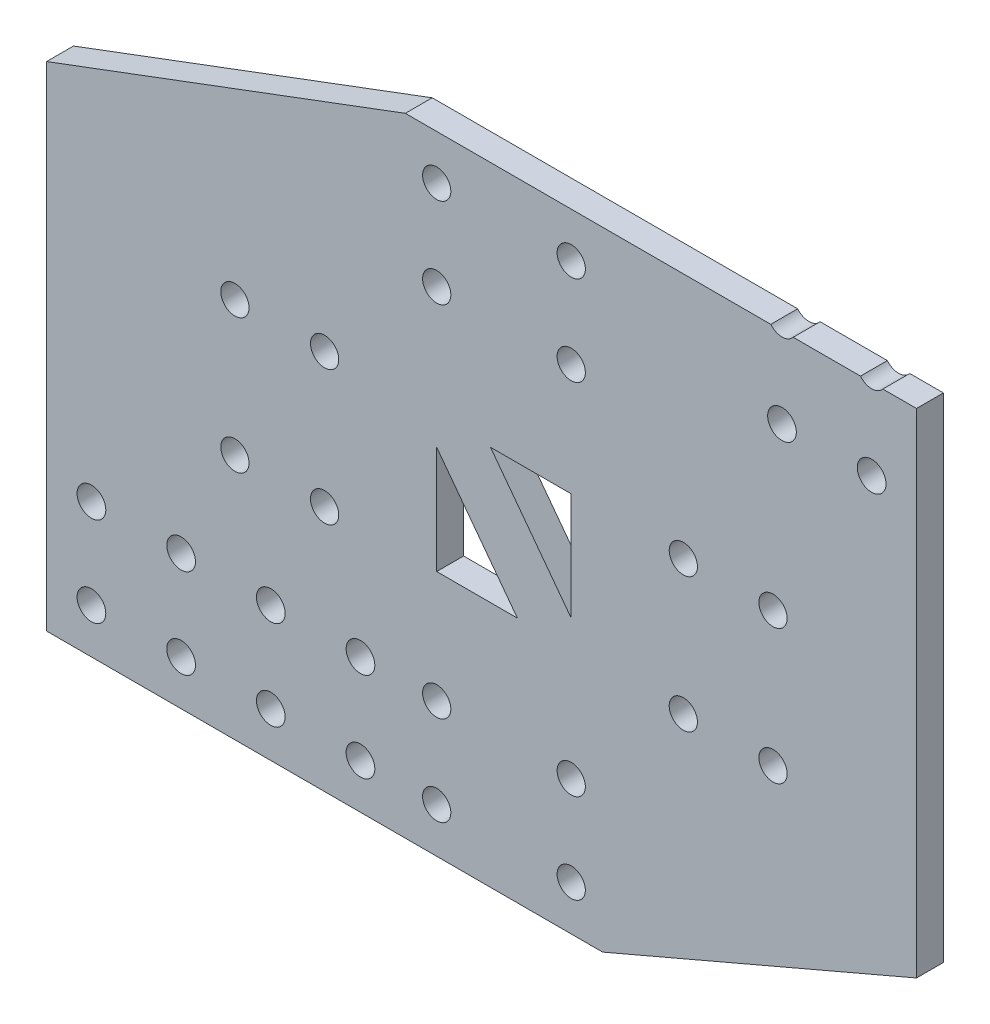
SolidWorks part; units mm, degrees
ref_plane "前视基准面" through (0, 0, 0) normal (0, 0, 1) x (1, 0, 0)
ref_plane "上视基准面" through (0, 0, 0) normal (0, 1, 0) x (1, 0, 0)
ref_plane "右视基准面" through (0, 0, 0) normal (1, 0, 0) x (0, 0, -1)
other "Configuration Table"
sketch "草图1" plane through (0, 0, 0) normal (0, 0, 1) x (1, 0, 0)
  line L0 (0, 0) -> (22, 0)
  line L2 (22, -70) -> (0, -70)
  line L4 (-40, -55) -> (-40, -15)
  line L5 (-40, -15) -> (0, 0)
  line L6 (-40, -35) -> (57, -35) construction
  line L7 (0, 0) -> (0, -70) construction
  line L9 (57, -15) -> (57, -55)
  line L10 (57, -55) -> (22, -70)
  line L11 (22, 0) -> (22, -35) construction
  line L12 (-40, -55) -> (-40, -70)
  line L13 (-40, -70) -> (0, -70)
  line L14 (22, 0) -> (57, 0)
  line L15 (57, 0) -> (57, -15)
  dimension "D1" = 22
  dimension "D2" = 22
  dimension "D3" = 40
  dimension "D4" = 40
  dimension "D5" = 40
  dimension "D6" = 70
  dimension "D7" = 35
extrude "凸台-拉伸1" add sketch "草图1" along normal blind 3
sketch "草图2" plane through (0, 0, 3) normal (0, 0, 1) x (1, 0, 0)
  line L0 (11, 0) -> (11, -70) construction
  line L1 (57, -4) -> (-40, -4) construction
  line L2 (-10, -70) -> (-10, -60) construction
  line L3 (57, -10) -> (11, -10) construction
  line L4 (36, -35) -> (36, -70) construction
  line L5 (57, -35) -> (-40, -35) construction
  line L7 (-14, -35) -> (-14, -70) construction
  line L8 (47, 0) -> (47, -35) construction
  line L9 (0, 0) -> (0, -70) construction
  line L10 (57, 0) -> (0, 0) construction
  line L20 (3.5, -30.5) -> (3.5, -42.5)
  line L21 (3.5, -42.5) -> (12.5, -42.5)
  line L22 (12.5, -42.5) -> (3.5, -30.5)
  line L23 (9.5, -27.5) -> (18.5, -39.5)
  line L24 (18.5, -39.5) -> (18.5, -27.5)
  line L25 (18.5, -27.5) -> (9.5, -27.5)
  line L28 (-40, -70) -> (22, -70) construction
  line L29 (57, -55) -> (57, 0) construction
  line L30 (-40, -15) -> (-40, -70) construction
  line L31 (0, -60) -> (-40, -60) construction
  line L32 (-20, -60) -> (-20, -70) construction
  line L33 (-30, -70) -> (-30, -60) construction
  circle A0 centre (18.5, -5) radius 1.575
  circle A1 centre (18.5, -15) radius 1.575
  circle A2 centre (3.5, -15) radius 1.575
  circle A3 centre (3.5, -5) radius 1.575
  circle A4 centre (3.5, -65) radius 1.575
  circle A5 centre (3.5, -55) radius 1.575
  circle A6 centre (18.5, -55) radius 1.575
  circle A7 centre (18.5, -65) radius 1.575
  circle A8 centre (-19, -42.5) radius 1.575
  circle A9 centre (-19, -27.5) radius 1.575
  circle A10 centre (-9, -42.5) radius 1.575
  circle A11 centre (-9, -27.5) radius 1.575
  circle A16 centre (31, -42.5) radius 1.575
  circle A17 centre (41, -42.5) radius 1.575
  circle A18 centre (41, -27.5) radius 1.575
  circle A19 centre (31, -27.5) radius 1.575
  circle A20 centre (-35, -65) radius 1.6
  circle A21 centre (-25, -65) radius 1.6
  circle A22 centre (-25, -55) radius 1.6
  circle A23 centre (-35, -55) radius 1.6
  circle A24 centre (-5, -55) radius 1.6
  circle A25 centre (-15, -55) radius 1.6
  circle A26 centre (-15, -65) radius 1.6
  circle A27 centre (-5, -65) radius 1.6
  circle A32 centre (52, 1) radius 1.6
  circle A33 centre (42, 1) radius 1.6
  circle A34 centre (52, -9) radius 1.6
  circle A35 centre (42, -9) radius 1.6
  dimension "D2" = 3.15
  dimension "D6" = 3.15
  dimension "D11" = 10
  dimension "D21" = 3.2
  dimension "D24" = 3.2
  dimension "D3" = 5
  dimension "D4" = 7.5
  dimension "D5" = 50
  dimension "D7" = 5
  dimension "D8" = 7.5
  dimension "D9" = 11
  dimension "D10" = 10
  dimension "D12" = 5
  dimension "D13" = 7.5
  dimension "D14" = 9
  dimension "D15" = 12
  dimension "D16" = 9
  dimension "D17" = 12
  dimension "D18" = 15
  dimension "D19" = 7.5
  dimension "D20" = 5
  dimension "D22" = 31
  dimension "D23" = 10
  dimension "D25" = 5
  dimension "D26" = 5
  dimension "D27" = 10
extrude "切除-拉伸1" cut sketch "草图2" against normal through all
